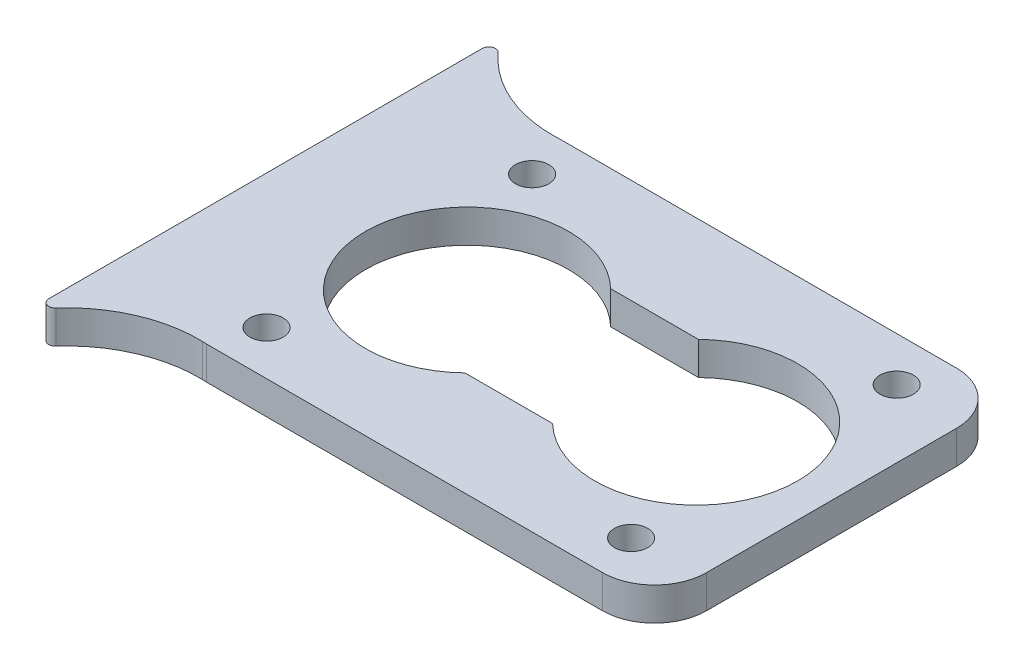
SolidWorks part; units mm, degrees
material "Custom Plastic"
ref_plane "X-Y Datum" through (0, 0, 0) normal (0, 0, 1) x (1, 0, 0)
ref_plane "X-Z Datum" through (0, 0, 0) normal (0, 1, 0) x (1, 0, 0)
ref_plane "Y-Z Datum" through (0, 0, 0) normal (1, 0, 0) x (0, 0, -1)
sketch "Sketch1" plane through (0, 0, 0) normal (0, 1, 0) x (1, 0, 0)
  line L0 (-157.7346, 34.7035) -> (-119.7346, 34.7035)
  line L1 (-162.7346, 63.7035) -> (-162.7346, 39.7035)
  line L2 (-119.7346, 68.7035) -> (-157.7346, 68.7035)
  line L3 (-114.7346, 39.7035) -> (-114.7346, 63.7035)
  line L4 (-134.5216, 44.7035) -> (-142.9477, 44.7035)
  line L5 (-142.9477, 58.7035) -> (-134.5216, 58.7035)
  arc A0 (-119.7346, 34.7035) -> (-114.7346, 39.7035) centre (-119.7346, 39.7035) ccw
  arc A1 (-162.7346, 39.7035) -> (-157.7346, 34.7035) centre (-157.7346, 39.7035) ccw
  arc A2 (-157.7346, 68.7035) -> (-162.7346, 63.7035) centre (-157.7346, 63.7035) ccw
  arc A3 (-114.7346, 63.7035) -> (-119.7346, 68.7035) centre (-119.7346, 63.7035) ccw
  arc A4 (-134.5216, 44.7035) -> (-127.7346, 41.9535) centre (-127.7346, 51.7035) ccw
  arc A5 (-149.7346, 41.9535) -> (-142.9477, 44.7035) centre (-149.7346, 51.7035) ccw
  arc A6 (-149.7346, 61.4535) -> (-149.7346, 41.9535) centre (-149.7346, 51.7035) ccw
  arc A7 (-142.9477, 58.7035) -> (-149.7346, 61.4535) centre (-149.7346, 51.7035) ccw
  arc A8 (-127.7346, 61.4535) -> (-134.5216, 58.7035) centre (-127.7346, 51.7035) ccw
  arc A9 (-127.7346, 41.9535) -> (-127.7346, 61.4535) centre (-127.7346, 51.7035) ccw
  arc A10 (-121.2346, 37.3535) -> (-121.2346, 40.5535) centre (-121.2346, 38.9535) ccw
  arc A11 (-121.2346, 40.5535) -> (-121.2346, 37.3535) centre (-121.2346, 38.9535) ccw
  arc A12 (-156.2346, 37.3535) -> (-156.2346, 40.5535) centre (-156.2346, 38.9535) ccw
  arc A13 (-156.2346, 40.5535) -> (-156.2346, 37.3535) centre (-156.2346, 38.9535) ccw
  arc A14 (-156.2346, 62.8535) -> (-156.2346, 66.0535) centre (-156.2346, 64.4535) ccw
  arc A15 (-156.2346, 66.0535) -> (-156.2346, 62.8535) centre (-156.2346, 64.4535) ccw
  arc A16 (-121.2346, 62.8535) -> (-121.2346, 66.0535) centre (-121.2346, 64.4535) ccw
  arc A17 (-121.2346, 66.0535) -> (-121.2346, 62.8535) centre (-121.2346, 64.4535) ccw
  point P43 (0, 0)
  point P44 (-121.2346, 66.0535)
  point P45 (-143.3391, 44.8482)
  point P47 (-121.238, 63.1663)
  dimension "D4" = 1.6
  dimension "D5" = 9.75
  dimension "D6" = 9.75
  dimension "D8" = 9.75
  dimension "D9" = 9.75
  dimension "D12" = 5
  dimension "D15" = 5
  dimension "D18" = 38
  dimension "D34" = 3.2
  dimension "D1" = 22
  dimension "D2" = 6.5
  dimension "D3" = 28.5
  dimension "D7" = 14
  dimension "D10" = 8.4261
  dimension "D11" = 6.7869
  dimension "D13" = 8
  dimension "D14" = 38
  dimension "D16" = 24
  dimension "D17" = 24
  dimension "D19" = 51.7035
  dimension "D20" = 149.7346
  dimension "D21" = 7
  dimension "D22" = 9.75
  dimension "D23" = 7
  dimension "D24" = 6.7869
  dimension "D25" = 19.5
  dimension "D26" = 19.5
  dimension "D27" = 6.7869
  dimension "D28" = 14
  dimension "D29" = 16.75
  dimension "D30" = 12.75
  dimension "D31" = 12.75
  dimension "D32" = 12.75
  dimension "D33" = 12.75
  dimension "D35" = 6.5
extrude "Boss-Extrude1" add sketch "Sketch1" along normal blind 3.175
sketch "Sketch2" plane through (0, 0, 0) normal (0, -1, 0) x (1, 0, 0)
  line L2 (-162.7346, -51.7035) -> (-114.7346, -51.7035) construction
  line L6 (-162.7346, -63.7035) -> (-162.7346, -39.7035) construction
  line L9 (-119.7346, -68.7035) -> (-157.7346, -68.7035) construction
  line L10 (-119.7346, -68.7035) -> (-157.7346, -68.7035)
  line L11 (-114.7346, -39.7035) -> (-114.7346, -63.7035) construction
  line L12 (-169.0846, -74.3821) -> (-169.0846, -29.0249)
  line L13 (-162.7346, -63.7035) -> (-162.7346, -39.7035)
  arc A6 (-169.0846, -74.3821) -> (-157.7346, -68.7035) centre (-158.4873, -81.3812) cw
  arc A7 (-162.7346, -63.7035) -> (-157.7346, -68.7035) centre (-157.7346, -63.7035) ccw construction
  arc A8 (-162.7346, -63.7035) -> (-157.7346, -68.7035) centre (-157.7346, -63.7035) ccw
  arc A9 (-162.7346, -39.7035) -> (-157.7346, -34.7035) centre (-157.7346, -39.7035) cw
  arc A10 (-169.0846, -29.0249) -> (-157.7346, -34.7035) centre (-158.4873, -22.0258) ccw
  point P19 (-169.0846, -51.7035)
  dimension "D1" = 12.7
  dimension "D2" = 6.35
  dimension "D3" = 22.6786
extrude "Boss-Extrude2" add sketch "Sketch2" against normal blind 3.175
fillet "Fillet1" radius 0.635 2 edges at (-169.0846, 1.5875, -29.0249) (-169.0846, 1.5875, -74.3821)
